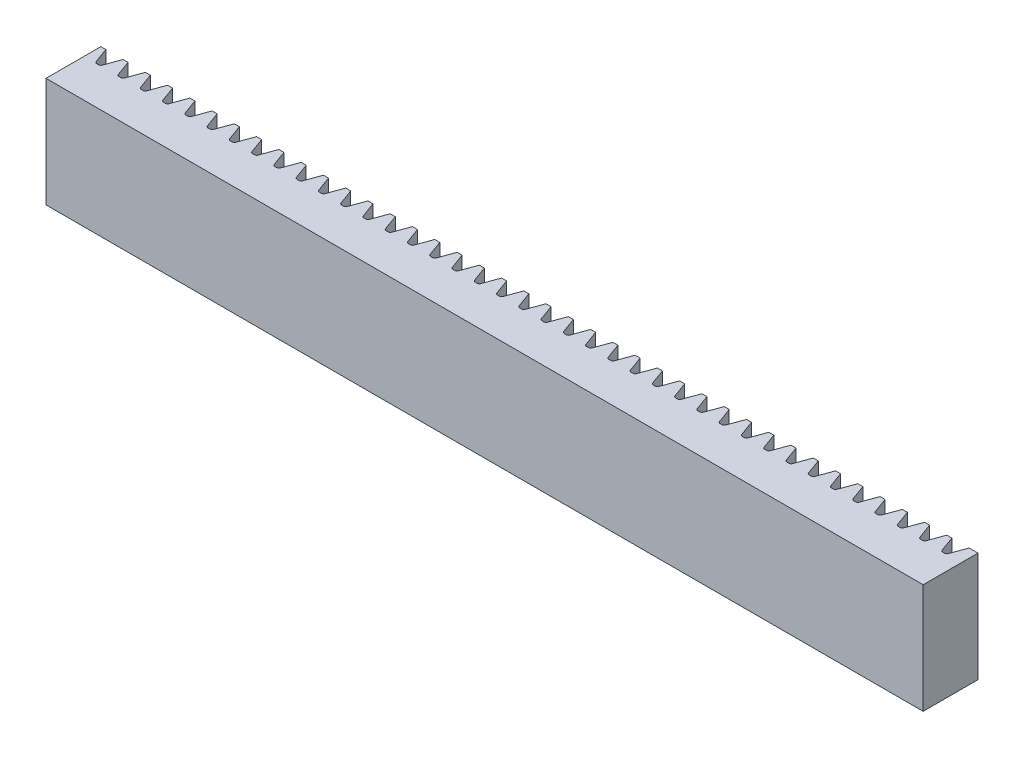
SolidWorks part; units mm, degrees
ref_plane "Front Plane" through (0, 0, 0) normal (0, 0, 1) x (1, 0, 0)
ref_plane "Top Plane" through (0, 0, 0) normal (0, 1, 0) x (1, 0, 0)
ref_plane "Right Plane" through (0, 0, 0) normal (1, 0, 0) x (0, 0, -1)
sketch "Sketch1" plane through (0, 0, 0) normal (0, 1, 0) x (1, 0, 0)
  line L0 (0, 6.35) -> (120, 6.35) construction
  line L1 (0, 0) -> (120, 0)
  line L2 (0, 0) -> (0, 7.5)
  line L3 (0, 7.5) -> (120, 7.5) construction
  line L4 (120, 0) -> (120, 7.5)
  line L5 (0, 5.2) -> (120, 5.2) construction
  line L6 (0, 7.5) -> (0.6858, 7.5)
  line L7 (0.6858, 7.5) -> (1.5229, 5.2)
  line L8 (1.5229, 5.2) -> (2.2087, 5.2)
  line L9 (1.8658, 5.2) -> (1.8658, 7.5) construction
  line L10 (3.0459, 7.5) -> (2.2087, 5.2)
  line L168 (3.0459, 7.5) -> (3.7317, 7.5)
  line L169 (3.7317, 7.5) -> (4.5688, 5.2)
  line L170 (4.5688, 5.2) -> (5.2546, 5.2)
  line L171 (6.0917, 7.5) -> (5.2546, 5.2)
  line L172 (6.0917, 7.5) -> (6.7775, 7.5)
  line L173 (6.7775, 7.5) -> (7.6147, 5.2)
  line L174 (7.6147, 5.2) -> (8.3005, 5.2)
  line L175 (9.1376, 7.5) -> (8.3005, 5.2)
  line L176 (9.1376, 7.5) -> (9.8234, 7.5)
  line L177 (9.8234, 7.5) -> (10.6605, 5.2)
  line L178 (10.6605, 5.2) -> (11.3463, 5.2)
  line L179 (12.1835, 7.5) -> (11.3463, 5.2)
  line L180 (12.1835, 7.5) -> (12.8693, 7.5)
  line L181 (12.8693, 7.5) -> (13.7064, 5.2)
  line L182 (13.7064, 5.2) -> (14.3922, 5.2)
  line L183 (15.2293, 7.5) -> (14.3922, 5.2)
  line L184 (15.2293, 7.5) -> (15.9151, 7.5)
  line L185 (15.9151, 7.5) -> (16.7522, 5.2)
  line L186 (16.7522, 5.2) -> (17.438, 5.2)
  line L187 (18.2752, 7.5) -> (17.438, 5.2)
  line L188 (18.2752, 7.5) -> (18.961, 7.5)
  line L189 (18.961, 7.5) -> (19.7981, 5.2)
  line L190 (19.7981, 5.2) -> (20.4839, 5.2)
  line L191 (21.321, 7.5) -> (20.4839, 5.2)
  line L192 (21.321, 7.5) -> (22.0068, 7.5)
  line L193 (22.0068, 7.5) -> (22.844, 5.2)
  line L194 (22.844, 5.2) -> (23.5298, 5.2)
  line L195 (24.3669, 7.5) -> (23.5298, 5.2)
  line L196 (24.3669, 7.5) -> (25.0527, 7.5)
  line L197 (25.0527, 7.5) -> (25.8898, 5.2)
  line L198 (25.8898, 5.2) -> (26.5756, 5.2)
  line L199 (27.4128, 7.5) -> (26.5756, 5.2)
  line L200 (27.4128, 7.5) -> (28.0986, 7.5)
  line L201 (28.0986, 7.5) -> (28.9357, 5.2)
  line L202 (28.9357, 5.2) -> (29.6215, 5.2)
  line L203 (120, 7.5) -> (118.7887, 7.5)
  line L204 (30.4586, 7.5) -> (29.6215, 5.2)
  line L205 (30.4586, 7.5) -> (31.1444, 7.5)
  line L206 (31.1444, 7.5) -> (31.9816, 5.2)
  line L207 (31.9816, 5.2) -> (32.6674, 5.2)
  line L208 (33.5045, 7.5) -> (32.6674, 5.2)
  line L209 (33.5045, 7.5) -> (34.1903, 7.5)
  line L210 (34.1903, 7.5) -> (35.0274, 5.2)
  line L211 (35.0274, 5.2) -> (35.7132, 5.2)
  line L212 (36.5504, 7.5) -> (35.7132, 5.2)
  line L213 (36.5504, 7.5) -> (37.2362, 7.5)
  line L214 (37.2362, 7.5) -> (38.0733, 5.2)
  line L215 (38.0733, 5.2) -> (38.7591, 5.2)
  line L216 (39.5962, 7.5) -> (38.7591, 5.2)
  line L217 (39.5962, 7.5) -> (40.282, 7.5)
  line L218 (40.282, 7.5) -> (41.1192, 5.2)
  line L219 (41.1192, 5.2) -> (41.805, 5.2)
  line L220 (42.6421, 7.5) -> (41.805, 5.2)
  line L221 (42.6421, 7.5) -> (43.3279, 7.5)
  line L222 (43.3279, 7.5) -> (44.165, 5.2)
  line L223 (44.165, 5.2) -> (44.8508, 5.2)
  line L224 (45.6879, 7.5) -> (44.8508, 5.2)
  line L225 (45.6879, 7.5) -> (46.3737, 7.5)
  line L226 (46.3737, 7.5) -> (47.2109, 5.2)
  line L227 (47.2109, 5.2) -> (47.8967, 5.2)
  line L228 (48.7338, 7.5) -> (47.8967, 5.2)
  line L229 (48.7338, 7.5) -> (49.4196, 7.5)
  line L230 (49.4196, 7.5) -> (50.2567, 5.2)
  line L231 (50.2567, 5.2) -> (50.9425, 5.2)
  line L232 (51.7797, 7.5) -> (50.9425, 5.2)
  line L233 (51.7797, 7.5) -> (52.4655, 7.5)
  line L234 (52.4655, 7.5) -> (53.3026, 5.2)
  line L235 (53.3026, 5.2) -> (53.9884, 5.2)
  line L236 (54.8255, 7.5) -> (53.9884, 5.2)
  line L237 (54.8255, 7.5) -> (55.5113, 7.5)
  line L238 (55.5113, 7.5) -> (56.3485, 5.2)
  line L239 (56.3485, 5.2) -> (57.0343, 5.2)
  line L240 (57.8714, 7.5) -> (57.0343, 5.2)
  line L241 (57.8714, 7.5) -> (58.5572, 7.5)
  line L242 (58.5572, 7.5) -> (59.3943, 5.2)
  line L243 (59.3943, 5.2) -> (60.0801, 5.2)
  line L244 (60.9173, 7.5) -> (60.0801, 5.2)
  line L245 (60.9173, 7.5) -> (61.6031, 7.5)
  line L246 (61.6031, 7.5) -> (62.4402, 5.2)
  line L247 (62.4402, 5.2) -> (63.126, 5.2)
  line L248 (63.9631, 7.5) -> (63.126, 5.2)
  line L249 (63.9631, 7.5) -> (64.6489, 7.5)
  line L250 (64.6489, 7.5) -> (65.4861, 5.2)
  line L251 (65.4861, 5.2) -> (66.1719, 5.2)
  line L252 (67.009, 7.5) -> (66.1719, 5.2)
  line L253 (67.009, 7.5) -> (67.6948, 7.5)
  line L254 (67.6948, 7.5) -> (68.5319, 5.2)
  line L255 (68.5319, 5.2) -> (69.2177, 5.2)
  line L256 (70.0549, 7.5) -> (69.2177, 5.2)
  line L257 (70.0549, 7.5) -> (70.7407, 7.5)
  line L258 (70.7407, 7.5) -> (71.5778, 5.2)
  line L259 (71.5778, 5.2) -> (72.2636, 5.2)
  line L260 (73.1007, 7.5) -> (72.2636, 5.2)
  line L261 (73.1007, 7.5) -> (73.7865, 7.5)
  line L262 (73.7865, 7.5) -> (74.6236, 5.2)
  line L263 (74.6236, 5.2) -> (75.3094, 5.2)
  line L264 (76.1466, 7.5) -> (75.3094, 5.2)
  line L265 (76.1466, 7.5) -> (76.8324, 7.5)
  line L266 (76.8324, 7.5) -> (77.6695, 5.2)
  line L267 (77.6695, 5.2) -> (78.3553, 5.2)
  line L268 (79.1924, 7.5) -> (78.3553, 5.2)
  line L269 (79.1924, 7.5) -> (79.8782, 7.5)
  line L270 (79.8782, 7.5) -> (80.7154, 5.2)
  line L271 (80.7154, 5.2) -> (81.4012, 5.2)
  line L272 (82.2383, 7.5) -> (81.4012, 5.2)
  line L273 (82.2383, 7.5) -> (82.9241, 7.5)
  line L274 (82.9241, 7.5) -> (83.7612, 5.2)
  line L275 (83.7612, 5.2) -> (84.447, 5.2)
  line L276 (85.2842, 7.5) -> (84.447, 5.2)
  line L277 (85.2842, 7.5) -> (85.97, 7.5)
  line L278 (85.97, 7.5) -> (86.8071, 5.2)
  line L279 (86.8071, 5.2) -> (87.4929, 5.2)
  line L280 (88.33, 7.5) -> (87.4929, 5.2)
  line L281 (88.33, 7.5) -> (89.0158, 7.5)
  line L282 (89.0158, 7.5) -> (89.853, 5.2)
  line L283 (89.853, 5.2) -> (90.5388, 5.2)
  line L284 (91.3759, 7.5) -> (90.5388, 5.2)
  line L285 (91.3759, 7.5) -> (92.0617, 7.5)
  line L286 (92.0617, 7.5) -> (92.8988, 5.2)
  line L287 (92.8988, 5.2) -> (93.5846, 5.2)
  line L288 (94.4218, 7.5) -> (93.5846, 5.2)
  line L289 (94.4218, 7.5) -> (95.1076, 7.5)
  line L290 (95.1076, 7.5) -> (95.9447, 5.2)
  line L291 (95.9447, 5.2) -> (96.6305, 5.2)
  line L292 (97.4676, 7.5) -> (96.6305, 5.2)
  line L293 (97.4676, 7.5) -> (98.1534, 7.5)
  line L294 (98.1534, 7.5) -> (98.9906, 5.2)
  line L295 (98.9906, 5.2) -> (99.6764, 5.2)
  line L296 (100.5135, 7.5) -> (99.6764, 5.2)
  line L297 (100.5135, 7.5) -> (101.1993, 7.5)
  line L298 (101.1993, 7.5) -> (102.0364, 5.2)
  line L299 (102.0364, 5.2) -> (102.7222, 5.2)
  line L300 (103.5593, 7.5) -> (102.7222, 5.2)
  line L301 (103.5593, 7.5) -> (104.2451, 7.5)
  line L302 (104.2451, 7.5) -> (105.0823, 5.2)
  line L303 (105.0823, 5.2) -> (105.7681, 5.2)
  line L304 (106.6052, 7.5) -> (105.7681, 5.2)
  line L305 (106.6052, 7.5) -> (107.291, 7.5)
  line L306 (107.291, 7.5) -> (108.1281, 5.2)
  line L307 (108.1281, 5.2) -> (108.8139, 5.2)
  line L308 (109.6511, 7.5) -> (108.8139, 5.2)
  line L309 (109.6511, 7.5) -> (110.3369, 7.5)
  line L310 (110.3369, 7.5) -> (111.174, 5.2)
  line L311 (111.174, 5.2) -> (111.8598, 5.2)
  line L312 (112.6969, 7.5) -> (111.8598, 5.2)
  line L313 (112.6969, 7.5) -> (113.3827, 7.5)
  line L314 (113.3827, 7.5) -> (114.2199, 5.2)
  line L315 (114.2199, 5.2) -> (114.9057, 5.2)
  line L316 (115.7428, 7.5) -> (114.9057, 5.2)
  line L317 (115.7428, 7.5) -> (116.4286, 7.5)
  line L318 (116.4286, 7.5) -> (117.2657, 5.2)
  line L319 (117.2657, 5.2) -> (117.9515, 5.2)
  line L320 (118.7887, 7.5) -> (117.9515, 5.2)
  point P13 (118.8289, 7.5)
  point P15 (0, 0)
  dimension "D1" = 7.5
  dimension "D2" = 120
  dimension "D3" = 6.35
  dimension "D4" = 0.6858
  dimension "D5" = 110
  dimension "D6" = 0.3429
  dimension "D7" = 39
extrude "Boss-Extrude1" add sketch "Sketch1" along normal blind 15
fillet "Fillet1" radius 0.3 78 edges at (117.9515, 7.5, -5.2) (117.2657, 7.5, -5.2) (114.9057, 7.5, -5.2) (114.2199, 7.5, -5.2) (111.8598, 7.5, -5.2) (111.174, 7.5, -5.2) (108.8139, 7.5, -5.2) (108.1281, 7.5, -5.2) (105.7681, 7.5, -5.2) (105.0823, 7.5, -5.2) (102.7222, 7.5, -5.2) (102.0364, 7.5, -5.2) (99.6764, 7.5, -5.2) (98.9906, 7.5, -5.2) (96.6305, 7.5, -5.2) (95.9447, 7.5, -5.2) (93.5846, 7.5, -5.2) (92.8988, 7.5, -5.2) (90.5388, 7.5, -5.2) (89.853, 7.5, -5.2) (87.4929, 7.5, -5.2) (86.8071, 7.5, -5.2) (84.447, 7.5, -5.2) (83.7612, 7.5, -5.2) (81.4012, 7.5, -5.2) (80.7154, 7.5, -5.2) (78.3553, 7.5, -5.2) (77.6695, 7.5, -5.2) (75.3094, 7.5, -5.2) (74.6236, 7.5, -5.2) (72.2636, 7.5, -5.2) (71.5778, 7.5, -5.2) (69.2177, 7.5, -5.2) (68.5319, 7.5, -5.2) (66.1719, 7.5, -5.2) (65.4861, 7.5, -5.2) (63.126, 7.5, -5.2) (62.4402, 7.5, -5.2) (60.0801, 7.5, -5.2) (59.3943, 7.5, -5.2) (57.0343, 7.5, -5.2) (56.3485, 7.5, -5.2) (53.9884, 7.5, -5.2) (53.3026, 7.5, -5.2) (50.9425, 7.5, -5.2) (50.2567, 7.5, -5.2) (47.8967, 7.5, -5.2) (47.2109, 7.5, -5.2) (44.8508, 7.5, -5.2) (44.165, 7.5, -5.2) (41.805, 7.5, -5.2) (41.1192, 7.5, -5.2) (38.7591, 7.5, -5.2) (38.0733, 7.5, -5.2) (35.7132, 7.5, -5.2) (35.0274, 7.5, -5.2) (32.6674, 7.5, -5.2) (31.9816, 7.5, -5.2) (29.6215, 7.5, -5.2) (28.9357, 7.5, -5.2) (26.5756, 7.5, -5.2) (25.8898, 7.5, -5.2) (23.5298, 7.5, -5.2) (22.844, 7.5, -5.2) (20.4839, 7.5, -5.2) (19.7981, 7.5, -5.2) (17.438, 7.5, -5.2) (16.7522, 7.5, -5.2) (14.3922, 7.5, -5.2) (13.7064, 7.5, -5.2) (11.3463, 7.5, -5.2) (10.6605, 7.5, -5.2) (8.3005, 7.5, -5.2) (7.6147, 7.5, -5.2) (5.2546, 7.5, -5.2) (4.5688, 7.5, -5.2) (2.2087, 7.5, -5.2) (1.5229, 7.5, -5.2)
equation "\"bottomHalf\"=0.4"
equation "\"topWidth\"=0.06858"
equation "\"D4@Sketch1\"=\"topWidth\""
equation "\"D6@Sketch1\"=\"topWidth\"/2"
